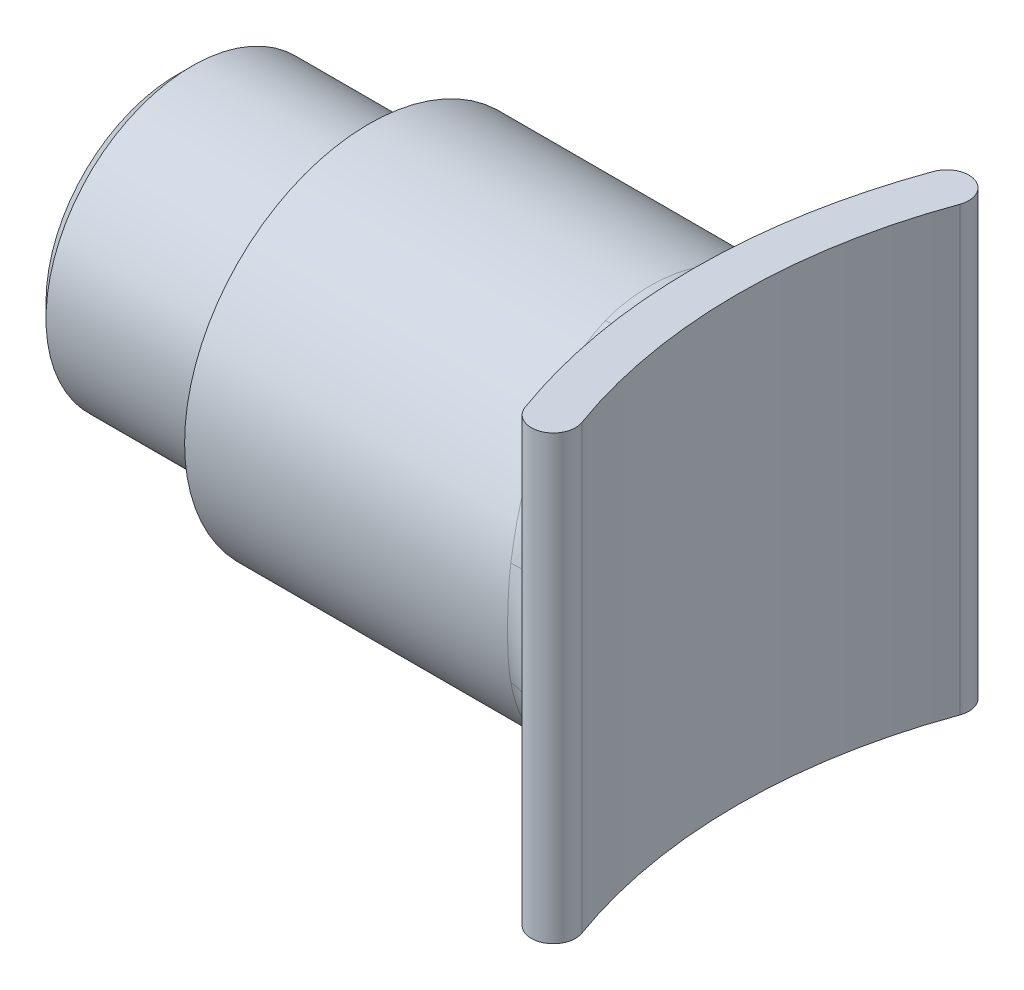
SolidWorks part; units mm, degrees
ref_plane "Front Plane" through (0, 0, 0) normal (0, 0, 1) x (1, 0, 0)
ref_plane "Top Plane" through (0, 0, 0) normal (0, 1, 0) x (1, 0, 0)
ref_plane "Right Plane" through (0, 0, 0) normal (1, 0, 0) x (0, 0, -1)
sketch "Sketch1" plane through (0, 0, 0) normal (0, 1, 0) x (1, 0, 0)
  line L0 (0, 0) -> (102.6669, 0) construction
  line L1 (37.5, 0) -> (-12.6066, 18.2373) construction
  arc A0 (2.2615, 12.8258) -> (2.2615, -12.8258) centre (37.5, 0) ccw
  arc A1 (-0.5576, 13.8518) -> (-0.5576, -13.8518) centre (37.5, 0) ccw
  arc A2 (2.2615, 12.8258) -> (-0.5576, 13.8518) centre (0.852, 13.3388) ccw
  arc A3 (2.2615, -12.8258) -> (-0.5576, -13.8518) centre (0.852, -13.3388) cw
  dimension "D1" = 75
  dimension "D2" = 20
  dimension "D3" = 3
extrude "Boss-Extrude1" add sketch "Sketch1" along normal mid plane 30
ref_plane "Plane1" through (-3, 0, 0) normal (-1, 0, 0) x (0, 0, 1)
sketch "Sketch2" plane through (-3, 0, 0) normal (-1, 0, 0) x (0, 0, 1)
  line L0 (0, 15) -> (0, -15) construction
  line L1 (13.8518, 15) -> (-13.8518, 15) construction
  line L2 (-13.8518, -15) -> (13.8518, -15) construction
  circle A0 centre (0, 0) radius 12.5
  dimension "D1" = 25
extrude "Boss-Extrude2" add sketch "Sketch2" along normal blind 22 and the other way up to surface other way up to face at (-1.7788, 0, 0)
sketch "Sketch3" plane through (-25, 0, 0) normal (-1, 0, 0) x (0, 0, 1)
  circle A0 centre (0, 0) radius 9.9
  dimension "D1" = 19.8
extrude "Boss-Extrude3" add sketch "Sketch3" along normal blind 13
chamfer "Chamfer1" distance 1 angle 45 1 edges at (-38, 0, 9.9)
fillet "Fillet7" radius 3 1 edges at (-1.0876, 2.236, 12.2984)
